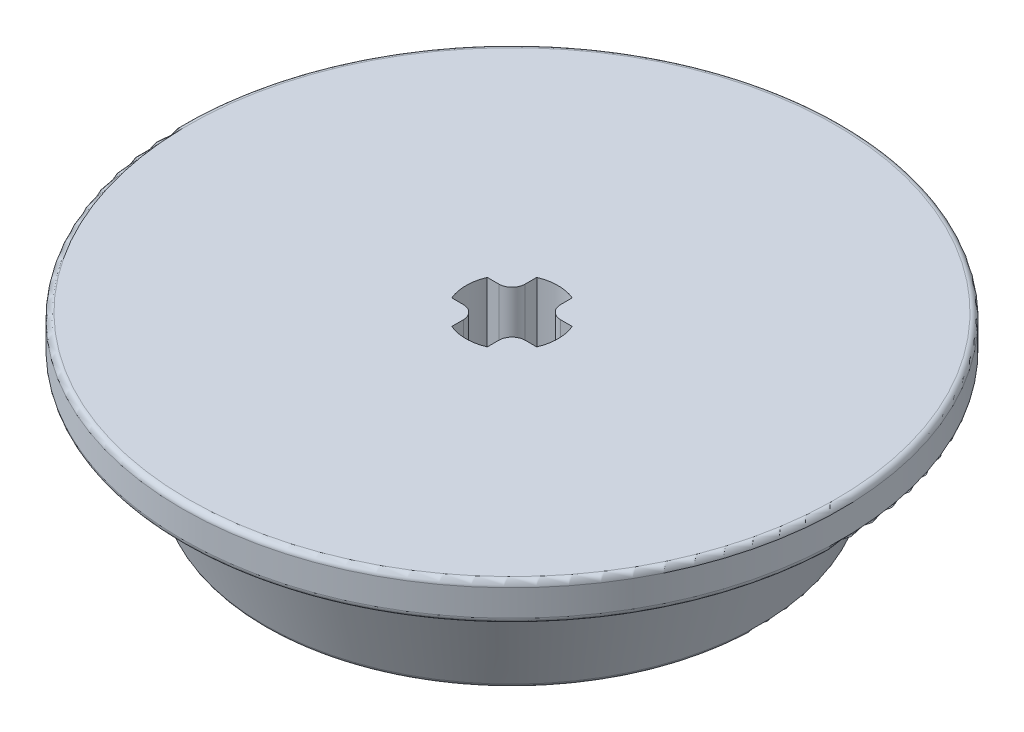
SolidWorks part; units mm, degrees
ref_plane "Front Plane" through (0, 0, 0) normal (0, 0, 1) x (1, 0, 0)
ref_plane "Top Plane" through (0, 0, 0) normal (0, 1, 0) x (1, 0, 0)
ref_plane "Right Plane" through (0, 0, 0) normal (1, 0, 0) x (0, 0, -1)
sketch "Sketch1" plane through (0, 0, 0) normal (0, 1, 0) x (1, 0, 0)
  line L2 (0, 0) -> (0, 47.5777) construction
  line L3 (0, 0) -> (50000, 0) construction
  line L6 (-0.89, 0.89) -> (0, 0) construction
  line L7 (0, 0) -> (0.89, 0.89) construction
  line L12 (2.39, 0) -> (2.39, 3.5727) construction
  line L13 (0, 2.39) -> (50000, 2.39) construction
  line L14 (-2.39, 0.4111) -> (-2.39, -49999.5889) construction
  line L15 (0.2318, -2.39) -> (-49999.7682, -2.39) construction
  line L16 (0, 0) -> (-0.89, -0.89) construction
  line L17 (0, 0) -> (0.89, -0.89) construction
  line L18 (-0.94, 0.94) -> (-2.2517, 0.94)
  line L19 (-2.2517, -0.94) -> (-0.94, -0.94)
  line L20 (-0.94, -0.94) -> (-0.94, -2.2517)
  line L21 (0.94, -2.2517) -> (0.94, -0.94)
  line L22 (0.94, -0.94) -> (2.2517, -0.94)
  line L23 (0.94, 0.94) -> (2.2517, 0.94)
  line L24 (0.94, 2.2517) -> (0.94, 0.94)
  line L25 (-0.94, 2.2517) -> (-0.94, 0.94)
  arc A4 (-2.2517, 0.94) -> (-2.2517, -0.94) centre (0, 0) ccw
  arc A5 (-0.94, -2.2517) -> (0.94, -2.2517) centre (0, 0) ccw
  arc A6 (2.2517, 0.94) -> (2.2517, -0.94) centre (0, 0) cw
  arc A7 (-0.94, 2.2517) -> (0.94, 2.2517) centre (0, 0) cw
  point P15 (0, 2.39)
  point P24 (2.39, 0)
  point P29 (-2.39, 0)
  point P30 (0, -2.39)
  line B0 (-0.89, 2.2181) -> (-0.89, 0.89) construction
  line B1 (-0.89, 0.89) -> (-2.2181, 0.89) construction
  line B2 (0.89, 2.2181) -> (0.89, 0.89) construction
  line B3 (0.89, 0.89) -> (2.2181, 0.89) construction
  line B4 (-2.2181, -0.89) -> (-0.89, -0.89) construction
  line B5 (-0.89, -0.89) -> (-0.89, -2.2181) construction
  line B6 (0.89, -2.2181) -> (0.89, -0.89) construction
  line B7 (0.89, -0.89) -> (2.2181, -0.89) construction
  arc B8 (-0.89, 2.2181) -> (0.89, 2.2181) centre (0, 0) cw construction
  arc B9 (-2.2181, 0.89) -> (-2.2181, -0.89) centre (0, 0) ccw construction
  arc B10 (2.2181, 0.89) -> (2.2181, -0.89) centre (0, 0) cw construction
  arc B11 (-0.89, -2.2181) -> (0.89, -2.2181) centre (0, 0) ccw construction
sketch_block_instance "Lego Axle - Unfilleted-1"
sketch_block "Lego Axle - Unfilleted" parameters "D1"=10.5762, "D2"=12.3972, "D3"=62.5785, "D4"=1.2287, "D5"=12.9019, "D6"=1.0841, "D7"=0.05
sketch "Sketch2" plane through (0, 0, 0) normal (0, 0, 1) x (1, 0, 0)
  line L0 (0, 0) -> (17.4605, 0)
  line L1 (200000.2318, 0) -> (-249999.7682, 0) construction
  line L2 (17.4605, 0) -> (17.4605, -2)
  line L3 (17.4605, -2) -> (15, -2)
  line L4 (15, -2) -> (13.0505, -8)
  line L5 (13.0505, -8) -> (0, -8)
  line L6 (0, -8) -> (0, 0)
  line L7 (0, 0) -> (0, 50000) construction
  dimension "D1" = 30
  dimension "D2" = 18
  dimension "D3" = 8
  dimension "D4" = 2
revolve "Revolve1" add sketch "Sketch2" angle 360 about L7
extrude "Cut-Extrude1" cut sketch "Sketch1" against normal through all
fillet "Fillet1" radius 0.7 4 edges at (-0.94, -4, 0.94) (0.94, -4, 0.94) (0.94, -4, -0.94) (-0.94, -4, -0.94)
fillet "Fillet2" radius 0.3 4 edges at (0, -8, -13.0505) (0, 0, -17.4605) (0, -2, -15) (0, -2, -17.4605)
